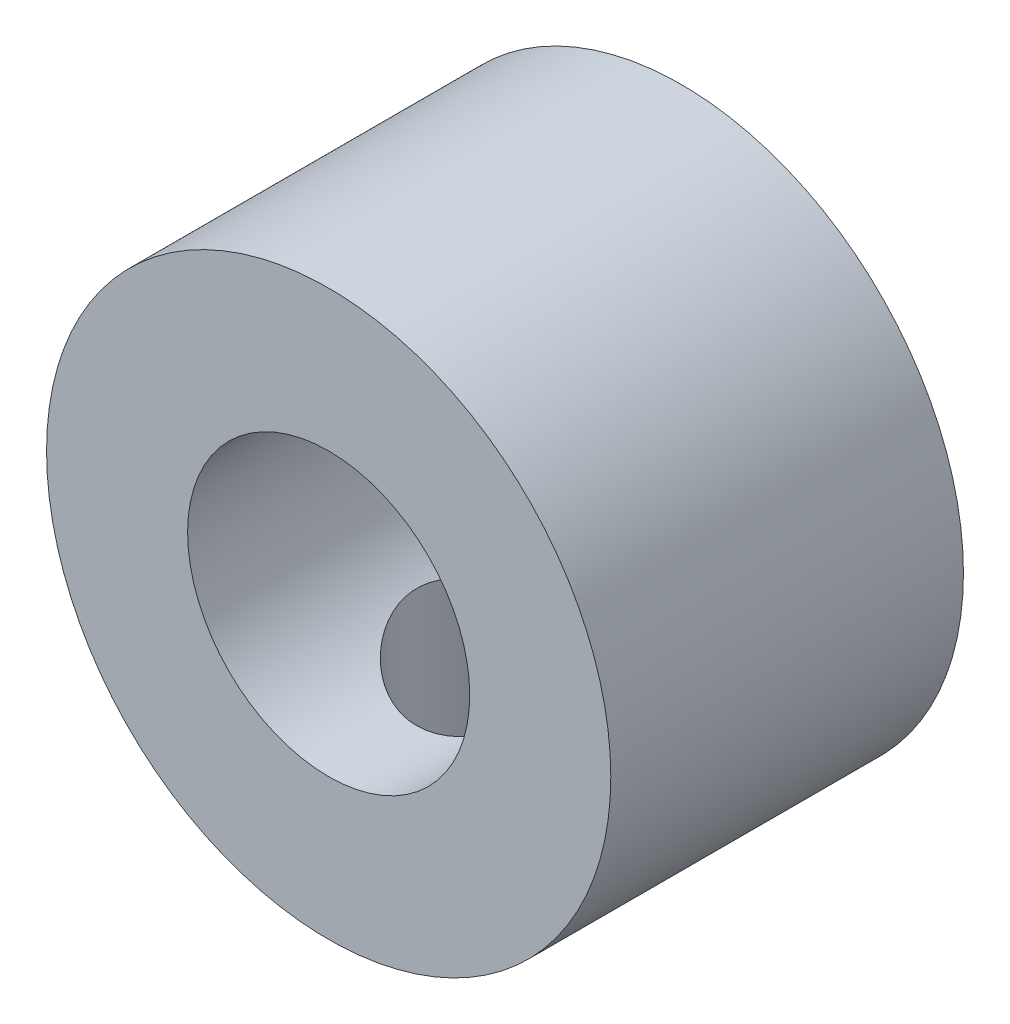
SolidWorks part; units mm, degrees
ref_plane "Plan de face" through (0, 0, 0) normal (0, 0, 1) x (1, 0, 0)
ref_plane "Plan de dessus" through (0, 0, 0) normal (0, 1, 0) x (1, 0, 0)
ref_plane "Plan de droite" through (0, 0, 0) normal (1, 0, 0) x (0, 0, -1)
sketch "Esquisse1" plane through (0, 0, 0) normal (0, 0, 1) x (1, 0, 0)
  circle A0 centre (0, 0) radius 4.8
  circle A1 centre (0, 0) radius 2.4
  dimension "D1" = 9.6
  dimension "D2" = 4.8
extrude "Boss.-Extru.3" add sketch "Esquisse1" along normal blind 6
sketch "Esquisse6" plane through (0, 0, 0) normal (0, 1, 0) x (1, 0, 0)
  line L0 (4.8, 0) -> (-4.8, 0) construction
  circle A0 centre (0, -3) radius 1.5
  dimension "D1" = 3
  dimension "D2" = 3
extrude "Enlèv. mat.-Extru.1" cut sketch "Esquisse6" against normal blind 6
